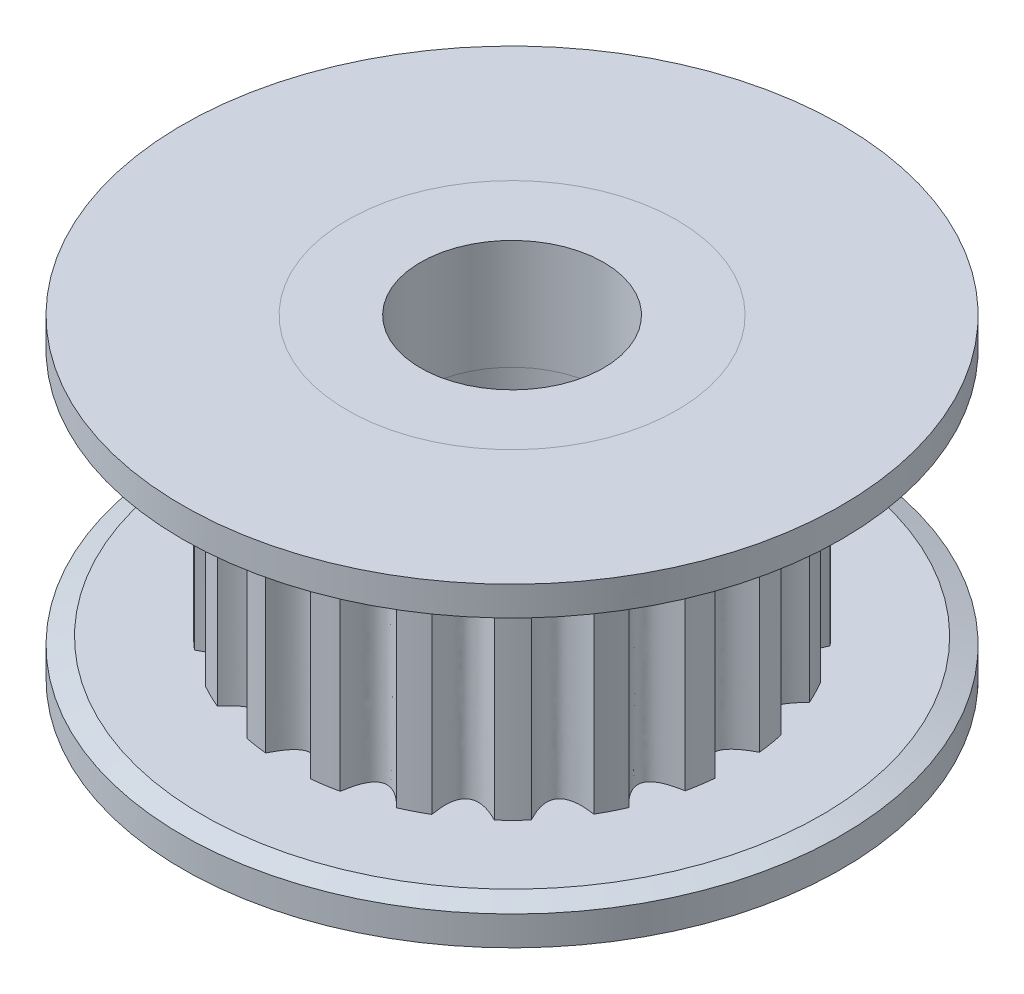
SolidWorks part; units mm, degrees
ref_plane "Plano frontal" through (0, 0, 0) normal (0, 0, 1) x (1, 0, 0)
ref_plane "Plano superior" through (0, 0, 0) normal (0, 1, 0) x (1, 0, 0)
ref_plane "Plano direito" through (0, 0, 0) normal (1, 0, 0) x (0, 0, -1)
sketch "Esboço1" plane through (0, 0, 0) normal (0, 0, 1) x (1, 0, 0)
  line L0 (-4.5, 0) -> (-9, 0)
  line L1 (-9, 0) -> (-9, 1)
  line L2 (-9, 1) -> (-6.15, 1)
  line L3 (-6.15, 1) -> (-6.15, 7.6)
  line L4 (-6.15, 7.6) -> (-9, 7.6)
  line L5 (-9, 7.6) -> (-9, 8.6)
  line L6 (-9, 8.6) -> (-4.5, 8.6)
  line L7 (-4.5, 0) -> (-4.5, 3)
  line L8 (-4.5, 3) -> (-2.5, 3)
  line L9 (-2.5, 3) -> (-2.5, 5.6)
  line L10 (-2.5, 5.6) -> (-4.5, 5.6)
  line L11 (-4.5, 5.6) -> (-4.5, 8.6)
  line L12 (0, 0) -> (0, 8.6) construction
  dimension "D1" = 1
  dimension "D2" = 9
  dimension "D3" = 6.6
  dimension "D4" = 6.15
  dimension "D5" = 4.5
  dimension "D6" = 2.5
  dimension "D7" = 3
revolve "Revolução1" add sketch "Esboço1" angle 360 about L12
chamfer "Chanfro1" distance 0.2 angle 70 1 edges at (0, 1, -9)
chamfer "Chanfro2" distance 0.2 angle 70 1 edges at (0, 7.6, -9)
sketch "Esboço2" plane through (0, 0, 0) normal (0, 0, 1) x (1, 0, 0)
  line L0 (-2.5, 0) -> (-2.5, 3)
  line L1 (-9, 0) -> (9, 0) construction
  line L2 (-2.5, 3) -> (-4.5, 3)
  line L3 (-4.5, 3) -> (-4.5, 0)
  line L4 (-4.5, 0) -> (-2.5, 0)
  line L5 (9, 8.6) -> (-9, 8.6) construction
  line L6 (-4.5, 5.6) -> (-2.5, 5.6)
  line L7 (-4.5, 5.6) -> (-4.5, 8.6)
  line L8 (-4.5, 8.6) -> (-2.5, 8.6)
  line L9 (-2.5, 5.6) -> (-2.5, 8.6)
  line L10 (0, 0) -> (0, 8.6) construction
  dimension "D1" = 2.5
  dimension "D2" = 4.5
  dimension "D3" = 3
revolve "Revolução2" add sketch "Esboço2" angle 360 about L10
sketch "Esboço3" plane through (0, 7.6, 0) normal (0, -1, 0) x (1, 0, 0)
  line L0 (0, 6.15) -> (0, 5.5) construction
  circle A0 centre (0, 0) radius 6.15 construction
  arc A1 (0.6113, 6.1195) -> (-0.6113, 6.1195) centre (0, 0) ccw
  arc A2 (2.4776, 5.6289) -> (1.3152, 6.0077) centre (0, 0) ccw
  arc A3 (4.0999, 4.584) -> (3.1122, 5.3044) centre (0, 0) ccw
  arc A4 (5.3186, 3.0878) -> (4.6028, 4.0788) centre (0, 0) ccw
  arc A5 (6.0137, 1.2876) -> (5.6402, 2.4517) centre (0, 0) ccw
  arc A6 (6.1167, -0.6394) -> (6.1223, 0.5832) centre (0, 0) ccw
  arc A7 (5.6174, -2.5034) -> (6.0016, -1.3428) centre (0, 0) ccw
  arc A8 (4.5651, -4.1209) -> (5.2901, -3.1365) centre (0, 0) ccw
  arc A9 (3.0634, -5.3328) -> (4.0577, -4.6215) centre (0, 0) ccw
  arc A10 (1.26, -6.0195) -> (2.4258, -5.6514) centre (0, 0) ccw
  arc A11 (-0.6674, -6.1137) -> (0.5551, -6.1249) centre (0, 0) ccw
  arc A12 (-2.5291, -5.6059) -> (-1.3703, -5.9954) centre (0, 0) ccw
  arc A13 (-4.1418, -4.5462) -> (-3.1608, -5.2756) centre (0, 0) ccw
  arc A14 (-5.3468, -3.0389) -> (-4.64, -4.0364) centre (0, 0) ccw
  arc A15 (-6.0253, -1.2324) -> (-5.6625, -2.3998) centre (0, 0) ccw
  arc A16 (-6.1105, 0.6955) -> (-6.1274, -0.5269) centre (0, 0) ccw
  arc A17 (-5.5942, 2.5548) -> (-5.989, 1.3978) centre (0, 0) ccw
  arc A18 (-4.5271, 4.1627) -> (-5.261, 3.185) centre (0, 0) ccw
  arc A19 (-3.0143, 5.3607) -> (-4.0151, 4.6585) centre (0, 0) ccw
  arc A20 (-1.2047, 6.0309) -> (-2.3738, 5.6734) centre (0, 0) ccw
  spline S0 degree 2 poles (0.6113, 6.1195) (0, 4.8805) (-0.6113, 6.1195) knots 0 0 0 1 1 1
  spline S1 degree 2 poles (2.4776, 5.6289) (1.5075, 4.6418) (1.3152, 6.0077) knots 0 0 0 1 1 1
  spline S2 degree 2 poles (4.0999, 4.584) (2.8676, 3.949) (3.1122, 5.3044) knots 0 0 0 1 1 1
  spline S3 degree 2 poles (5.3186, 3.0878) (3.9471, 2.8701) (4.6028, 4.0788) knots 0 0 0 1 1 1
  spline S4 degree 2 poles (6.0137, 1.2876) (4.6405, 1.5105) (5.6402, 2.4517) knots 0 0 0 1 1 1
  spline S5 degree 2 poles (6.1167, -0.6394) (4.8799, 0.0032) (6.1223, 0.5832) knots 0 0 0 1 1 1
  spline S6 degree 2 poles (5.6174, -2.5034) (4.642, -1.5042) (6.0016, -1.3428) knots 0 0 0 1 1 1
  spline S7 degree 2 poles (4.5651, -4.1209) (3.9501, -2.8643) (5.2901, -3.1365) knots 0 0 0 1 1 1
  spline S8 degree 2 poles (3.0634, -5.3328) (2.872, -3.9441) (4.0577, -4.6215) knots 0 0 0 1 1 1
  spline S9 degree 2 poles (1.26, -6.0195) (1.5132, -4.638) (2.4258, -5.6514) knots 0 0 0 1 1 1
  spline S10 degree 2 poles (-0.6674, -6.1137) (0.0066, -4.8782) (0.5551, -6.1249) knots 0 0 0 1 1 1
  spline S11 degree 2 poles (-2.5291, -5.6059) (-1.5004, -4.6412) (-1.3703, -5.9954) knots 0 0 0 1 1 1
  spline S12 degree 2 poles (-4.1418, -4.5462) (-2.8603, -3.9505) (-3.1608, -5.2756) knots 0 0 0 1 1 1
  spline S13 degree 2 poles (-5.3468, -3.0389) (-3.9402, -2.8735) (-4.64, -4.0364) knots 0 0 0 1 1 1
  spline S14 degree 2 poles (-6.0253, -1.2324) (-4.6345, -1.5158) (-5.6625, -2.3998) knots 0 0 0 1 1 1
  spline S15 degree 2 poles (-6.1105, 0.6955) (-4.8754, -0.0103) (-6.1274, -0.5269) knots 0 0 0 1 1 1
  spline S16 degree 2 poles (-5.5942, 2.5548) (-4.6395, 1.4959) (-5.989, 1.3978) knots 0 0 0 1 1 1
  spline S17 degree 2 poles (-4.5271, 4.1627) (-3.9501, 2.8553) (-5.261, 3.185) knots 0 0 0 1 1 1
  spline S18 degree 2 poles (-3.0143, 5.3607) (-2.8747, 3.9351) (-4.0151, 4.6585) knots 0 0 0 1 1 1
  spline S19 degree 2 poles (-1.2047, 6.0309) (-1.5185, 4.6297) (-2.3738, 5.6734) knots 0 0 0 1 1 1
  point P67 (0, 0)
  dimension "D1" = 0.65
  dimension "D3" = 0.6
  dimension "D2" = 20
extrude "Corte-extrusão1" cut sketch "Esboço3" along normal up to surface (6.6 mm away) up to face at (0, 1, -8.4505)
ref_point "Ponto1"
